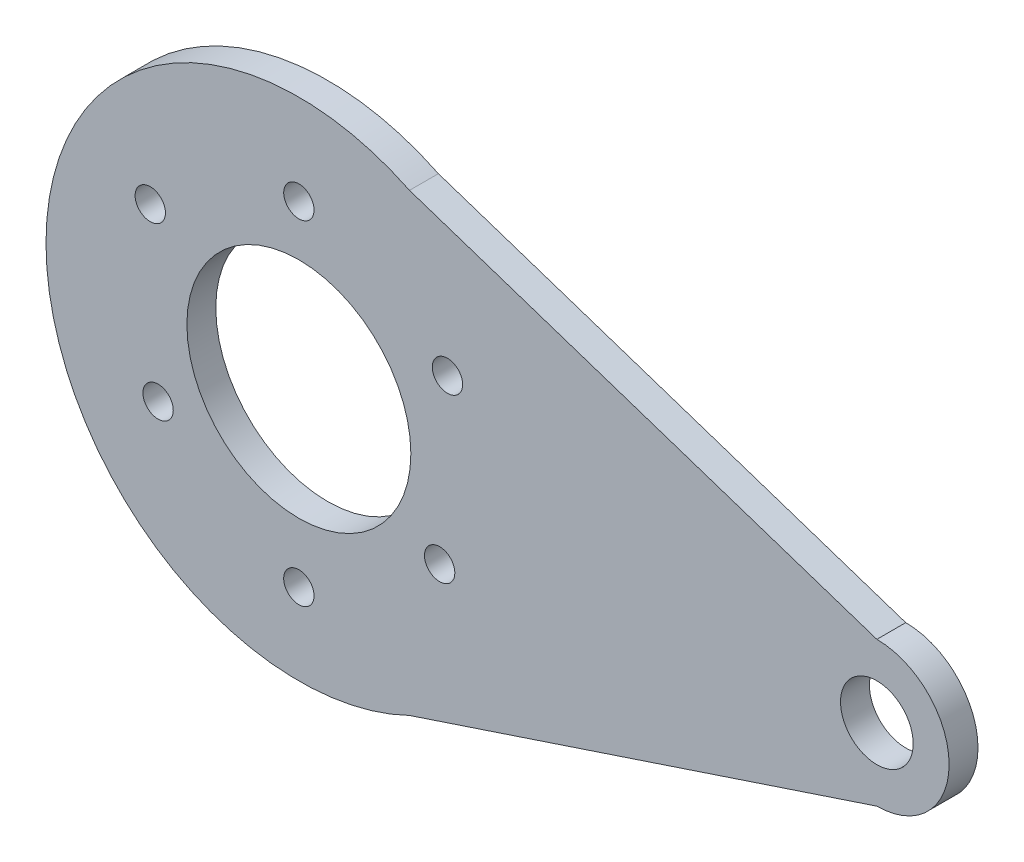
SolidWorks part; units mm, degrees
ref_plane "前视基准面" through (0, 0, 0) normal (0, 0, 1) x (1, 0, 0)
ref_plane "上视基准面" through (0, 0, 0) normal (0, 1, 0) x (1, 0, 0)
ref_plane "右视基准面" through (0, 0, 0) normal (1, 0, 0) x (0, 0, -1)
sketch "草图2" plane through (0, 0, 0) normal (0, 0, 1) x (1, 0, 0)
  line L0 (2.5741, -5.5276) -> (41.8465, -28.2015) construction
  line L1 (2.5741, -5.5276) -> (82.5741, -5.5276) construction
  line L5 (82.5741, 4.4724) -> (17.8866, 25.9451)
  line L6 (17.8866, -37.0002) -> (82.5741, -15.5276)
  circle A0 centre (2.5741, -5.5276) radius 23.75 construction
  circle A1 centre (2.5741, -5.5276) radius 22.5 construction
  circle A2 centre (2.5741, -29.2776) radius 2.1
  circle A3 centre (22.0596, -16.7776) radius 2.1
  circle A4 centre (2.5741, -5.5276) radius 35 construction
  arc A5 (17.8866, 25.9451) -> (17.8866, -37.0002) centre (2.5741, -5.5276) ccw
  circle A6 centre (2.5741, -5.5276) radius 15.5
  circle A11 centre (82.5741, -5.5276) radius 5.03
  circle A12 centre (82.5741, -5.5276) radius 10 construction
  arc A13 (82.5741, 4.4724) -> (82.5741, -15.5276) centre (82.5741, -5.5276) cw
  circle A14 centre (-17.994, 6.3474) radius 2.1
  circle A15 centre (23.1422, 6.3474) radius 2.1
  circle A16 centre (2.5741, 16.9724) radius 2.1
  circle A17 centre (-16.9115, -16.7776) radius 2.1
  dimension "D1" = 45
  dimension "D2" = 4.2
  dimension "D3" = 80
  dimension "D4" = 70
  dimension "D5" = 10.06
  dimension "D6" = 47.5
  dimension "D7" = 3
  dimension "D8" = 3
extrude "凸台-拉伸1" add sketch "草图2" along normal blind 4
